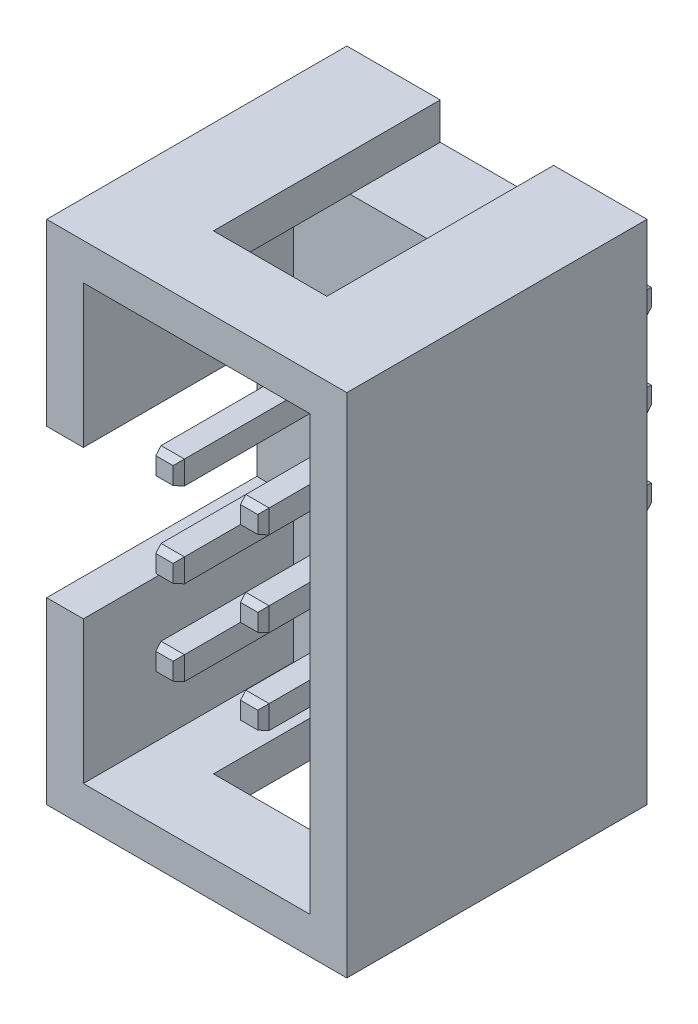
SolidWorks part; units mm, degrees
ref_plane "Plan de face" through (0, 0, 0) normal (0, 0, 1) x (1, 0, 0)
ref_plane "Plan de dessus" through (0, 0, 0) normal (0, 1, 0) x (1, 0, 0)
ref_plane "Plan de droite" through (0, 0, 0) normal (1, 0, 0) x (0, 0, -1)
sketch "Sketch1" plane through (0, 0, 0) normal (0, 0, 1) x (1, 0, 0)
  line L1 (-4.5, 7.6) -> (4.5, 7.6)
  line L2 (-4.5, 7.6) -> (-4.5, -7.6)
  line L3 (-4.5, -7.6) -> (4.5, -7.6)
  line L4 (4.5, 7.6) -> (4.5, -7.6)
  line L5 (-4.5, 7.6) -> (4.5, -7.6) construction
  line L6 (-4.5, -7.6) -> (4.5, 7.6) construction
  point P0 (0, 0)
  dimension "D1" = 15.2
  dimension "D2" = 9
extrude "Boss-Extrude1" add sketch "Sketch1" along normal blind 9
sketch "Sketch2" plane through (0, 0, 9) normal (0, 0, 1) x (1, 0, 0)
  line L12 (3.4, -6.5) -> (3.4, 6.5)
  line L13 (3.4, 6.5) -> (-3.4, 6.5)
  line L14 (-3.4, 6.5) -> (-3.4, -6.5)
  line L15 (-3.4, -6.5) -> (3.4, -6.5)
  line L16 (3.4, -6.5) -> (3.4, 6.5)
  line L17 (3.4, 6.5) -> (-3.4, 6.5)
  line L18 (-3.4, 6.5) -> (-3.4, -6.5)
  line L19 (-3.4, -6.5) -> (3.4, -6.5)
  dimension "D1" = 1.1
extrude "Cut-Extrude1" cut sketch "Sketch2" against normal blind 6.3
sketch "Sketch3" plane through (0, 0, 9) normal (0, 0, 1) x (1, 0, 0)
  line L0 (-4.5, 7.6) -> (-4.5, -7.6) construction
  line L1 (-4.5, 2.225) -> (-3.4, 2.225)
  line L2 (-4.5, 2.225) -> (-4.5, -2.225)
  line L3 (-4.5, -2.225) -> (-3.4, -2.225)
  line L4 (-3.4, 2.225) -> (-3.4, -2.225)
  line L5 (-3.4, 6.5) -> (-3.4, -6.5) construction
  line L6 (-3.4, 0) -> (0, 0) construction
  dimension "D1" = 4.45
extrude "Cut-Extrude2" cut sketch "Sketch3" against normal up to surface (6.3 mm away) up to face at (0, 0, 2.7)
sketch "Sketch4" plane through (0, -7.6, 0) normal (0, -1, 0) x (1, 0, 0)
  line L0 (-4.5, 0) -> (4.5, 0) construction
  line L1 (-1.7, 0) -> (1.7, 0)
  line L2 (-1.7, 0) -> (-1.7, 6.8)
  line L3 (-1.7, 6.8) -> (1.7, 6.8)
  line L4 (1.7, 0) -> (1.7, 6.8)
  line L5 (-4.5, 9) -> (4.5, 9) construction
  dimension "D1" = 2.2
  dimension "D2" = 3.4
extrude "Cut-Extrude3" cut sketch "Sketch4" against normal blind 1.1
mirror "Mirror1" about plane through (0, 0, 0) normal (0, 1, 0) of "Cut-Extrude3"
sketch "Sketch5" plane through (0, 0, 2.7) normal (0, 0, 1) x (1, 0, 0)
  line L1 (-1.62, 2.89) -> (-0.92, 2.89)
  line L2 (-1.62, 2.89) -> (-1.62, 2.19)
  line L3 (-1.62, 2.19) -> (-0.92, 2.19)
  line L4 (-0.92, 2.89) -> (-0.92, 2.19)
  line L5 (-1.62, 2.89) -> (-0.92, 2.19) construction
  line L6 (-1.62, 2.19) -> (-0.92, 2.89) construction
  point P0 (-1.27, 2.54)
  dimension "D1" = 0.7
  dimension "D2" = 2.54
  dimension "D3" = 1.27
extrude "Boss-Extrude2" add sketch "Sketch5" along normal blind 6 and the other way offset from surface (5.8 mm away) 3.1 other way up to face at (0, 0, 0)
pattern_linear "LPattern1" count 2 spacing 2.54 along (1, 0, 0) count 3 spacing 2.54 along (0, -1, 0) of "Boss-Extrude2"
chamfer "Chamfer1" distance 0.25 angle 20 48 edges at (1.27, 0.35, -3.1) (0.92, 0, -3.1) (1.27, -0.35, -3.1) (1.62, 0, -3.1) (1.27, 2.89, -3.1) (0.92, 2.54, -3.1) (1.27, 2.19, -3.1) (1.62, 2.54, -3.1) (-1.27, 2.89, -3.1) (-1.62, 2.54, -3.1) (-1.27, 2.19, -3.1) (-0.92, 2.54, -3.1) (-1.27, 0.35, -3.1) (-1.62, 0, -3.1) (-1.27, -0.35, -3.1) (-0.92, 0, -3.1) (-1.27, -2.19, -3.1) (-1.62, -2.54, -3.1) (-1.27, -2.89, -3.1) (-0.92, -2.54, -3.1) (1.27, -2.19, -3.1) (0.92, -2.54, -3.1) (1.27, -2.89, -3.1) (1.62, -2.54, -3.1) (1.27, -2.89, 8.7) (0.92, -2.54, 8.7) (1.27, -2.19, 8.7) (1.62, -2.54, 8.7) (-1.27, -2.89, 8.7) (-1.62, -2.54, 8.7) (-1.27, -2.19, 8.7) (-0.92, -2.54, 8.7) (-1.27, -0.35, 8.7) (-1.62, 0, 8.7) (-1.27, 0.35, 8.7) (-0.92, 0, 8.7) (1.27, -0.35, 8.7) (0.92, 0, 8.7) (1.27, 0.35, 8.7) (1.62, 0, 8.7) (1.27, 2.19, 8.7) (0.92, 2.54, 8.7) (1.27, 2.89, 8.7) (1.62, 2.54, 8.7) (-1.27, 2.19, 8.7) (-1.62, 2.54, 8.7) (-1.27, 2.89, 8.7) (-0.92, 2.54, 8.7)
